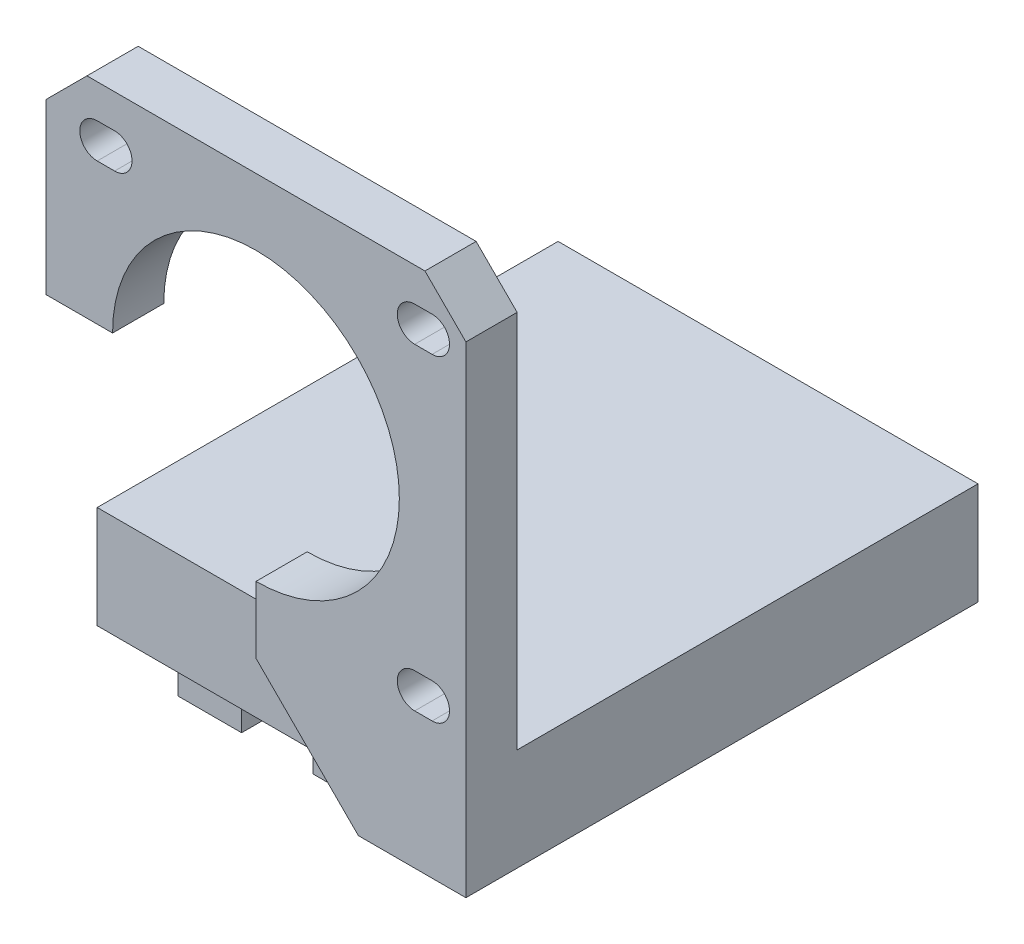
SolidWorks part; units mm, degrees
ref_plane "前视基准面" through (0, 0, 0) normal (0, 0, 1) x (1, 0, 0)
ref_plane "上视基准面" through (0, 0, 0) normal (0, 1, 0) x (1, 0, 0)
ref_plane "右视基准面" through (0, 0, 0) normal (1, 0, 0) x (0, 0, -1)
other "Configuration Table"
sketch "草图1" plane through (0, 0, 0) normal (0, 0, 1) x (1, 0, 0)
  line L20 (-20.5, 0) -> (-20.5, -16.5)
  line L21 (0, -20.5) -> (-16.5, -20.5)
  line L22 (-16.5, -20.5) -> (-20.5, -16.5)
  line L23 (0, -20.5) -> (16.5, -20.5)
  line L24 (20.5, 0) -> (20.5, -16.5)
  line L25 (20.5, -16.5) -> (16.5, -20.5)
  line L26 (20.5, 0) -> (20.5, 16.5)
  line L27 (0, 20.5) -> (16.5, 20.5)
  line L28 (16.5, 20.5) -> (20.5, 16.5)
  line L29 (0, 20.5) -> (-16.5, 20.5)
  line L30 (-20.5, 0) -> (-20.5, 16.5)
  line L31 (-20.5, 16.5) -> (-16.5, 20.5)
  circle A0 centre (0, 0) radius 11
  circle A1 centre (15.5, -15.5) radius 1.7
  circle A2 centre (15.5, 15.5) radius 1.7
  circle A3 centre (-15.5, 15.5) radius 1.7
  circle A4 centre (-15.5, -15.5) radius 1.7
extrude "凸台-拉伸1" add sketch "草图1" along normal blind 5 contours A0 | A4 | A3 | A2 | A1 | L29 L31 L30 L20 L22 L21 L23 L25 L24 L26 L28 L27
sketch "草图2" plane through (0, 0, 0) normal (0, 0, -1) x (-1, 0, 0)
  line L1 (-16.5, -30.5) -> (16.5, -30.5)
  line L2 (-16.5, -20.5) -> (16.5, -20.5)
  line L4 (20.5, -16.5) -> (20.5, -30.5)
  line L5 (20.5, -30.5) -> (16.5, -30.5)
  line L6 (16.5, -20.5) -> (20.5, -16.5)
  line L7 (-16.5, -20.5) -> (-20.5, -16.5)
  line L8 (-20.5, -16.5) -> (-20.5, -30.5)
  line L9 (-20.5, -30.5) -> (-16.5, -30.5)
extrude "凸台-拉伸2" add sketch "草图2" against normal blind 4 contours L2 L6 L4 L5 L1 L9 L8 L7
sketch "草图3" plane through (0, 0, 0) normal (0, 0, -1) x (-1, 0, 0)
  line L0 (-20.5, -30.5) -> (-20.5, -20.5)
  line L1 (-20.5, 16.5) -> (-20.5, -30.5) construction
  line L2 (-20.5, -20.5) -> (20.5, -20.5)
  line L3 (20.5, -30.5) -> (20.5, 16.5) construction
  line L4 (20.5, -20.5) -> (20.5, -30.5)
  line L5 (20.5, -30.5) -> (-20.5, -30.5)
extrude "凸台-拉伸3" add sketch "草图3" along normal blind 45 contours L5 L0 L2 L4
sketch "草图4" plane through (0, -30.5, 0) normal (0, -1, 0) x (1, 0, 0)
  line L5 (-13.6, -2.9084) -> (-13.6, 4)
  line L6 (-13.6, 4) -> (-7.4, 4)
  line L7 (-7.4, 4) -> (-7.4, -2.9084)
  line L12 (-13.6, -2.9084) -> (-13.6, -45)
  line L13 (-20.5, -45) -> (20.5, -45) construction
  line L14 (-7.4, -2.9084) -> (-7.4, -45)
  line L15 (-7.4, -45) -> (-13.6, -45)
extrude "凸台-拉伸4" add sketch "草图4" along normal blind 5 contours L7 L14 L15 L12 L5 L6
sketch "草图5" plane through (0, 0, 5) normal (0, 0, 1) x (1, 0, 0)
  line L0 (15.5, 17.2) -> (15.5, 13.8)
  line L1 (15.5, 13.8) -> (17.2, 13.8)
  line L4 (17.2, 17.2) -> (15.5, 17.2)
  line L5 (15.5, -13.8) -> (15.5, -17.2)
  line L6 (15.5, -17.2) -> (17.2, -17.2)
  line L9 (17.2, -13.8) -> (15.5, -13.8)
  line L10 (-15.5, -13.8) -> (-15.5, -17.2)
  line L11 (-15.5, -17.2) -> (-13.8, -17.2)
  line L14 (-13.8, -13.8) -> (-15.5, -13.8)
  line L15 (-15.5, 17.2) -> (-15.5, 13.8)
  line L16 (-15.5, 13.8) -> (-13.8, 13.8)
  line L18 (-13.8, 17.2) -> (-15.5, 17.2)
  circle A0 centre (15.5, 15.5) radius 1.7 construction
  arc A1 (17.2, 13.8) -> (17.2, 17.2) centre (17.2, 15.5) ccw
  circle A2 centre (15.5, -15.5) radius 1.7 construction
  arc A3 (17.2, -17.2) -> (17.2, -13.8) centre (17.2, -15.5) ccw
  circle A4 centre (-15.5, -15.5) radius 1.7 construction
  arc A5 (-13.8, -17.2) -> (-13.8, -13.8) centre (-13.8, -15.5) ccw
  circle A6 centre (-15.5, 15.5) radius 1.7 construction
  arc A7 (-13.8, 13.8) -> (-13.8, 17.2) centre (-13.8, 15.5) ccw
extrude "切除-拉伸1" cut sketch "草图5" against normal blind 5
sketch "草图6" plane through (0, -35.5, 0) normal (0, -1, 0) x (-1, 0, 0)
  line L0 (7.4, -4) -> (7.4, 45) construction
  line L1 (13.6, -4) -> (7.4, -4)
  line L2 (13.6, -4) -> (13.6, -1)
  line L3 (13.6, -1) -> (7.4, -1)
  line L4 (7.4, -4) -> (7.4, -1)
extrude "切除-拉伸2" cut sketch "草图6" against normal blind 5
sketch "草图8" plane through (0, 0, 5) normal (0, 0, 1) x (1, 0, 0)
  circle A0 centre (0, 0) radius 11.5
extrude "切除-拉伸3" cut sketch "草图8" against normal blind 5
sketch "草图9" plane through (0, -30.5, 0) normal (0, -1, 0) x (1, 0, 0)
  line L0 (-13.6, 1) -> (-20.5, 1)
  line L1 (-20.5, 4) -> (-20.5, -45) construction
  line L2 (-7.4, 1) -> (-0.5, 1)
  line L3 (-0.5, 1) -> (4.5, 1)
  line L4 (4.5, 1) -> (4.5, -45)
  line L5 (-7.4, -45) -> (20.5, -45) construction
  line L6 (4.5, -45) -> (-0.5, -45)
  line L7 (-0.5, -45) -> (-0.5, 1)
extrude "凸台-拉伸5" add sketch "草图9" along normal blind 5 contours L3 L4 L6 L7
sketch "草图10" plane through (0, 0, 5) normal (0, 0, 1) x (1, 0, 0)
  circle A0 centre (0, 0) radius 14
extrude "切除-拉伸4" cut sketch "草图10" against normal blind 5 contours A0
sketch "草图11" plane through (0, 0, 5) normal (0, 0, 1) x (1, 0, 0)
  line L0 (0, 0) -> (-20.5, 0)
  line L1 (-20.5, 16.5) -> (-20.5, -16.5) construction
  line L2 (-20.5, 0) -> (-20.5, -30.5)
  line L3 (0, 0) -> (0, -30.5)
  line L4 (20.5, -30.5) -> (-20.5, -30.5) construction
  line L5 (0, -30.5) -> (-20.5, -30.5)
extrude "切除-拉伸5" cut sketch "草图11" against normal blind 5 contours L5 L2 L0 L3
sketch "草图12" plane through (-13.6, 0, 0) normal (-1, 0, 0) x (0, 0, 1)
  line L0 (1, -35.5) -> (-45, -35.5) construction
  line L1 (1, -30.5) -> (0, -30.5)
  line L2 (1, -30.5) -> (1, -35.5)
  line L3 (1, -35.5) -> (0, -35.5)
  line L4 (0, -30.5) -> (0, -35.5)
extrude "切除-拉伸6" cut sketch "草图12" against normal blind 20 contours L2 L1 L4 L3
sketch "草图14" plane through (0, 0, 5) normal (0, 0, 1) x (1, 0, 0)
  line L0 (0, -20.5) -> (10, -30.5)
  line L1 (20.5, -30.5) -> (0, -30.5) construction
  line L2 (10, -30.5) -> (0, -30.5)
  line L3 (0, -30.5) -> (0, -20.5)
extrude "切除-拉伸7" cut sketch "草图14" against normal blind 5
sketch "草图15" plane through (0, 0, 4) normal (0, 0, 1) x (1, 0, 0)
  line L0 (0, -20.5) -> (10, -30.5)
  line L1 (10, -30.5) -> (20.5, -30.5)
  line L2 (20.5, -30.5) -> (20.5, -16.5)
  line L3 (20.5, -16.5) -> (16.5, -20.5)
  line L4 (16.5, -20.5) -> (0, -20.5)
extrude "凸台-拉伸6" add sketch "草图15" along normal blind 1
sketch "草图16" plane through (0, -35.5, 0) normal (0, -1, 0) x (1, 0, 0)
  line L0 (-20.5, -45) -> (-13.6, -45) construction
  line L1 (-13.6, 0) -> (-15.6, 0)
  line L2 (-13.6, 0) -> (-13.6, -45)
  line L3 (-13.6, -45) -> (-15.6, -45)
  line L4 (-15.6, 0) -> (-15.6, -45)
  line L5 (-7.4, -45) -> (-0.5, -45) construction
  line L6 (-0.5, 0) -> (-2.45, 0)
  line L7 (-0.5, 0) -> (-0.5, -45)
  line L8 (-0.5, -45) -> (-2.45, -45)
  line L9 (-2.45, 0) -> (-2.45, -45)
extrude "凸台-拉伸7" add sketch "草图16" against normal blind 5 contours L7 L6 L9 L8 | L2 L1 L4 L3
sketch "草图17" plane through (0, -35.5, 0) normal (0, -1, 0) x (1, 0, 0)
  line L0 (-7.4, -45) -> (-15.6, -45) construction
  line L1 (-7.4, 0) -> (-9.4, 0)
  line L2 (-7.4, 0) -> (-7.4, -45)
  line L3 (-7.4, -45) -> (-9.4, -45)
  line L4 (-9.4, 0) -> (-9.4, -45)
  line L5 (4.5, -45) -> (-2.45, -45) construction
  line L6 (4.5, 0) -> (2.5, 0)
  line L7 (4.5, 0) -> (4.5, -45)
  line L8 (4.5, -45) -> (2.5, -45)
  line L9 (2.5, 0) -> (2.5, -45)
  line L10 (-15.6, 0) -> (-15.6, -45) construction
  line L11 (4.5, 0) -> (-15.6, 0)
  line L12 (4.5, 0) -> (4.5, -3)
  line L13 (4.5, -3) -> (-15.6, -3)
  line L14 (-15.6, 0) -> (-15.6, -3)
  line M10 (-7.4, -45) -> (-7.4, 0)
  line M11 (-7.4, 0) -> (-15.6, 0)
  line M12 (-15.6, 0) -> (-15.6, -45)
  line M13 (-15.6, -45) -> (-7.4, -45)
extrude "切除-拉伸8" cut sketch "草图17" against normal blind 5 contours L13 L4 M10 M13 | L13 L2 L4 M11 | L13 L4 M11 M12 | L13 L9 L11 L2 | L13 L7 L6 L9 | L7 L13 L9 L8
